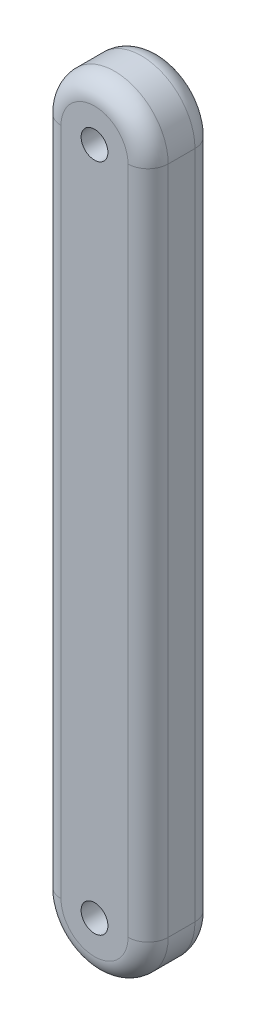
SolidWorks part; units mm, degrees
ref_plane "Front Plane" through (0, 0, 0) normal (0, 0, 1) x (1, 0, 0)
ref_plane "Top Plane" through (0, 0, 0) normal (0, 1, 0) x (1, 0, 0)
ref_plane "Right Plane" through (0, 0, 0) normal (1, 0, 0) x (0, 0, -1)
sketch "Sketch2" plane through (0, 0, 0) normal (0, 0, 1) x (1, 0, 0)
  line L0 (0, 50) -> (0, -50) construction
  line L1 (8, 50) -> (8, -50)
  line L2 (-8, 50) -> (-8, -50)
  arc A0 (8, 50) -> (-8, 50) centre (0, 50) ccw
  arc A1 (-8, -50) -> (8, -50) centre (0, -50) ccw
  circle A2 centre (0, 50) radius 2
  circle A3 centre (0, -50) radius 2
  point P2 (0, 0)
  dimension "D2" = 8
  dimension "D3" = 4
  dimension "D4" = 4
  dimension "D1" = 100
extrude "Boss-Extrude1" add sketch "Sketch2" along normal blind 10
fillet "Fillet2" radius 3 8 edges at (0, -58, 10) (-8, 0, 10) (0, 58, 10) (0, -58, 0) (-8, 0, 0) (0, 58, 0) (8, 0, 10) (8, 0, 0)
